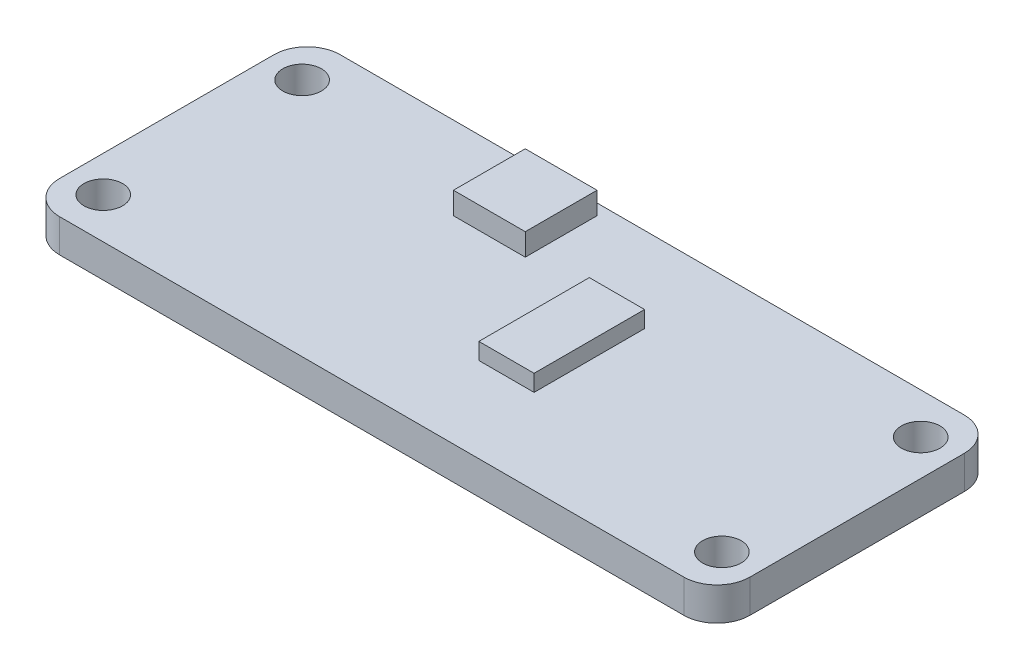
SolidWorks part; units mm, degrees
ref_plane "Front Plane" through (0, 0, 0) normal (0, 0, 1) x (1, 0, 0)
ref_plane "Top Plane" through (0, 0, 0) normal (0, 1, 0) x (1, 0, 0)
ref_plane "Right Plane" through (0, 0, 0) normal (1, 0, 0) x (0, 0, -1)
sketch "Sketch1" plane through (0, 0, 0) normal (0, 1, 0) x (1, 0, 0)
  line L1 (-31.25, 12.7) -> (31.25, 12.7)
  line L2 (-31.25, 12.7) -> (-31.25, -12.7)
  line L3 (-31.25, -12.7) -> (31.25, -12.7)
  line L4 (31.25, 12.7) -> (31.25, -12.7)
  line L5 (-31.25, 12.7) -> (31.25, -12.7) construction
  line L6 (-31.25, -12.7) -> (31.25, 12.7) construction
  point P0 (0, 0)
  dimension "D1" = 62.5
  dimension "D2" = 25.4
extrude "Boss-Extrude1" add sketch "Sketch1" along normal blind 3
fillet "Fillet1" radius 3 4 edges at (-31.25, 1.5, -12.7) (31.25, 1.5, -12.7) (31.25, 1.5, 12.7) (-31.25, 1.5, 12.7)
sketch "Sketch2" plane through (0, 3, 0) normal (0, 1, 0) x (1, 0, 0)
  line L1 (-28, 9) -> (28, 9) construction
  line L2 (-28, 9) -> (-28, -9) construction
  line L3 (-28, -9) -> (28, -9) construction
  line L4 (28, 9) -> (28, -9) construction
  line L5 (-28, 9) -> (28, -9) construction
  line L6 (-28, -9) -> (28, 9) construction
  circle A0 centre (-28, 9) radius 1.75
  circle A1 centre (28, 9) radius 1.75
  circle A2 centre (28, -9) radius 1.75
  circle A3 centre (-28, -9) radius 1.75
  point P0 (0, 0)
  dimension "D3" = 3.5
  dimension "D1" = 56
  dimension "D2" = 18
extrude "Cut-Extrude1" cut sketch "Sketch2" against normal through all
sketch "Sketch6" plane through (0, 3, 0) normal (0, 1, 0) x (1, 0, 0)
  line L0 (28.25, 12.7) -> (-28.25, 12.7) construction
  line L1 (-10.5, 11.7) -> (-4, 11.7)
  line L2 (-10.5, 11.7) -> (-10.5, 5.2)
  line L3 (-10.5, 5.2) -> (-4, 5.2)
  line L4 (-4, 11.7) -> (-4, 5.2)
  line L5 (-10.5, 11.7) -> (-4, 5.2) construction
  line L6 (-10.5, 5.2) -> (-4, 11.7) construction
  point P0 (-7.25, 8.45)
  dimension "D1" = 6.5
  dimension "D2" = 1
  dimension "D3" = 4
extrude "Boss-Extrude2" add sketch "Sketch6" along normal blind 2
sketch "Sketch7" plane through (0, 3, 0) normal (0, 1, 0) x (1, 0, 0)
  line L1 (2, 5) -> (7, 5)
  line L2 (2, 5) -> (2, -5)
  line L3 (2, -5) -> (7, -5)
  line L4 (7, 5) -> (7, -5)
  line L5 (2, 5) -> (7, -5) construction
  line L6 (2, -5) -> (7, 5) construction
  point P0 (4.5, 0)
  dimension "D1" = 5
  dimension "D2" = 10
  dimension "D3" = 2
extrude "Boss-Extrude3" add sketch "Sketch7" along normal blind 1.5
